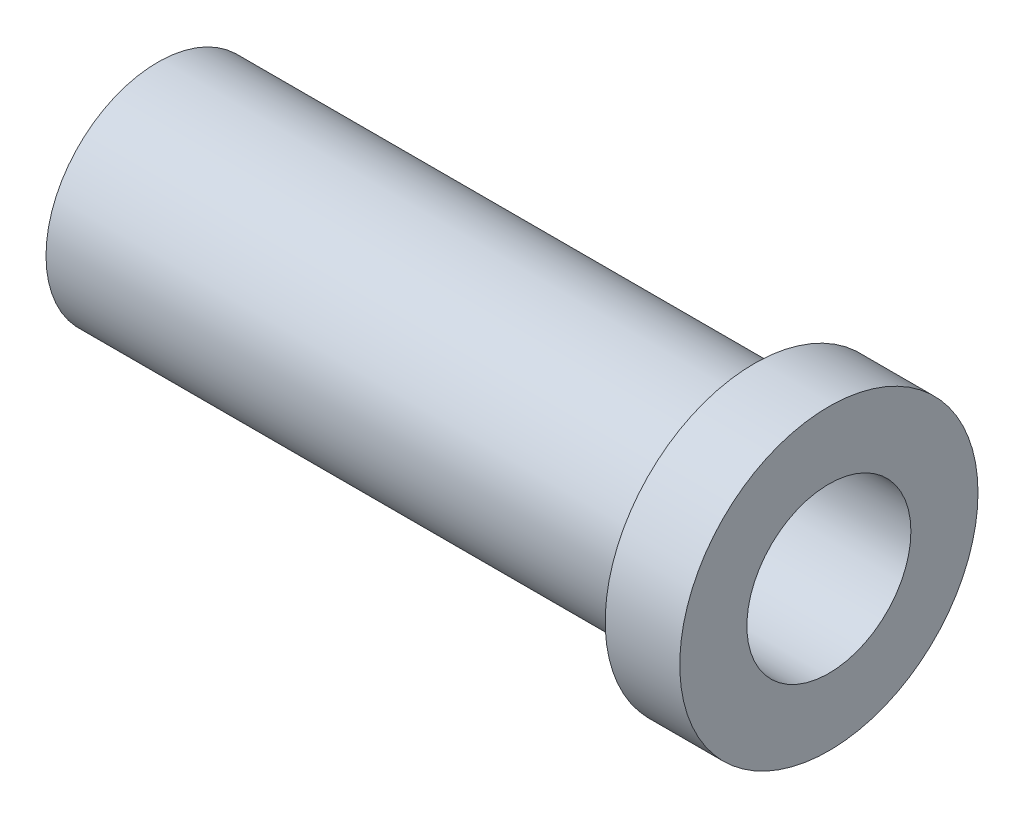
SolidWorks part; units mm, degrees
ref_plane "Front Plane" through (0, 0, 0) normal (0, 0, 1) x (1, 0, 0)
ref_plane "Top Plane" through (0, 0, 0) normal (0, 1, 0) x (1, 0, 0)
ref_plane "Right Plane" through (0, 0, 0) normal (1, 0, 0) x (0, 0, -1)
sketch "Sketch2" plane through (0, 0, 0) normal (1, 0, 0) x (0, 0, -1)
  circle A0 centre (0, 0) radius 10
  dimension "D1" = 20
extrude "Boss-Extrude1" add sketch "Sketch2" along normal blind 5
sketch "Sketch3" plane through (0, 0, 0) normal (-1, 0, 0) x (0, 0, 1)
  circle A0 centre (0, 0) radius 7.5
  dimension "D1" = 15
extrude "Boss-Extrude2" add sketch "Sketch3" along normal blind 40
sketch "Sketch6" plane through (5, 0, 0) normal (1, 0, 0) x (0, 0, -1)
  circle A0 centre (0, 0) radius 5.5
  dimension "D1" = 11
extrude "Cut-Extrude1" cut sketch "Sketch6" against normal through all
